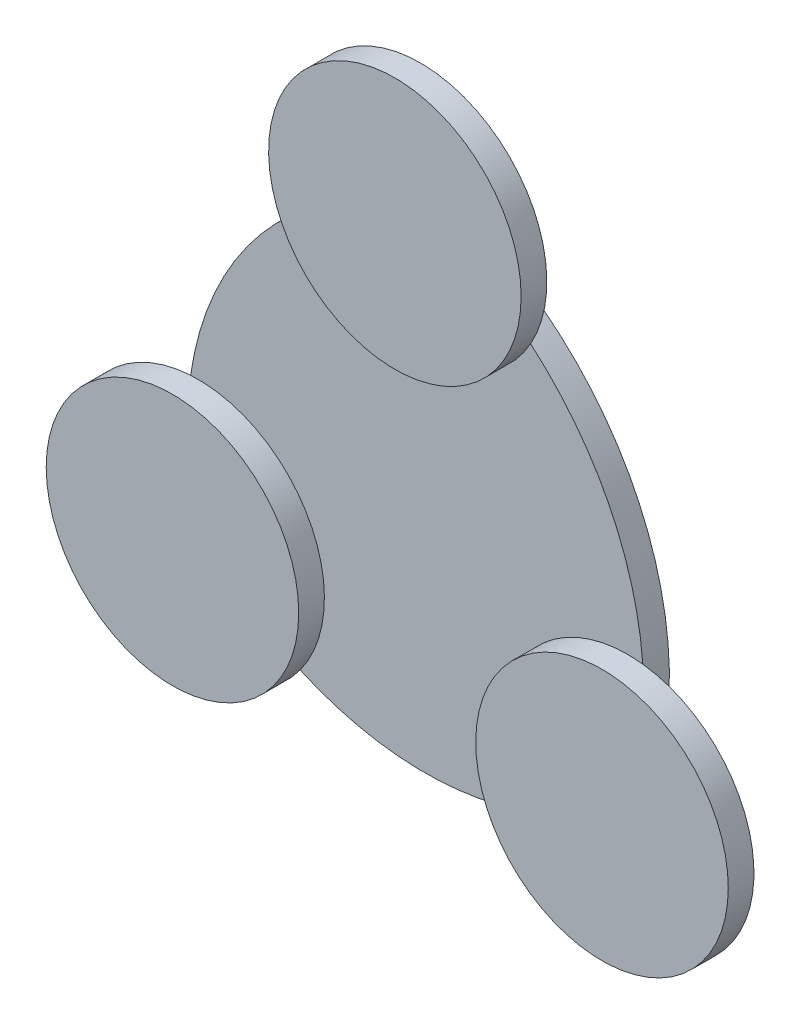
SolidWorks part; units mm, degrees
material "Cast Alloy Steel"
ref_plane "Front Plane" through (0, 0, 0) normal (0, 0, 1) x (1, 0, 0)
ref_plane "Top Plane" through (0, 0, 0) normal (0, 1, 0) x (1, 0, 0)
ref_plane "Right Plane" through (0, 0, 0) normal (1, 0, 0) x (0, 0, -1)
sketch "Sketch1" plane through (0, 0, 0) normal (0, 0, 1) x (1, 0, 0)
  line L0 (0, 0) -> (0, 30) construction
  line L1 (0, 0) -> (24.1974, -17.7337) construction
  line L2 (0, 0) -> (-25.9808, -15) construction
  arc A0 (0, 30) -> (24.1974, -17.7337) centre (-11.7682, -5.9656) cw
  arc A1 (24.1974, -17.7337) -> (-25.9808, -15) centre (0.4752, 8.7222) cw
  arc A2 (0, 30) -> (-25.9808, -15) centre (9.5096, -5.4904) ccw
  dimension "D1" = 120
  dimension "D2" = 126.237
  dimension "D3" = 30
  dimension "D4" = 30
  dimension "D5" = 30
extrude "Boss-Extrude1" add sketch "Sketch1" along normal blind 3
sketch "Sketch2" plane through (0, 0, 3) normal (0, 0, 1) x (1, 0, 0)
  circle A0 centre (0, 30) radius 14.75
  circle A1 centre (24.1974, -17.7337) radius 14.75
  circle A2 centre (-25.9808, -15) radius 14.75
  dimension "D1" = 29.5
  dimension "D2" = 29.5
  dimension "D3" = 29.5
extrude "Boss-Extrude2" add sketch "Sketch2" along normal blind 3
sketch "Sketch5" plane through (0, 0, 0) normal (0, 0, -1) x (-1, 0, 0)
  circle A0 centre (0, 0) radius 14.75
  circle A1 centre (0, 0) radius 15.25
  dimension "D1" = 29.5
  dimension "D2" = 30.5
extrude "Boss-Extrude3" add sketch "Sketch5" along normal blind 3
